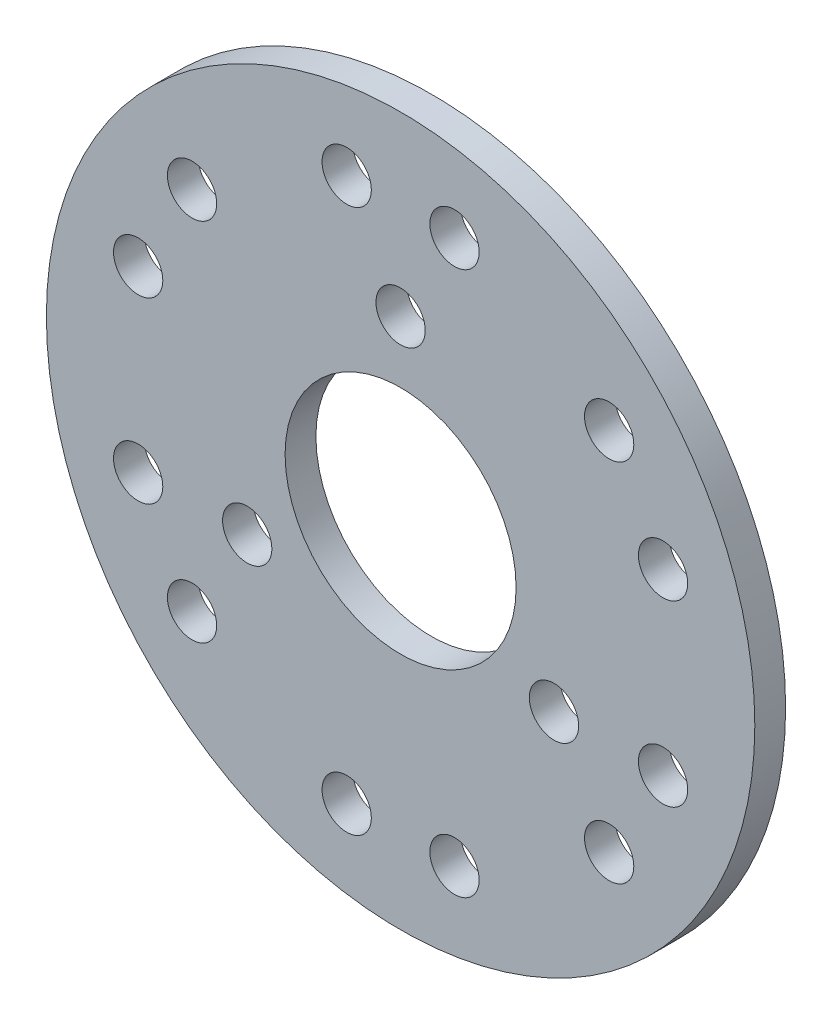
SolidWorks part; units mm, degrees
material "6061 合金"
ref_plane "正面" through (0, 0, 0) normal (0, 0, 1) x (1, 0, 0)
ref_plane "平面" through (0, 0, 0) normal (0, 1, 0) x (1, 0, 0)
ref_plane "右側面" through (0, 0, 0) normal (1, 0, 0) x (0, 0, -1)
sketch "ｽｹｯﾁ1" plane through (0, 0, 0) normal (0, 0, 1) x (1, 0, 0)
  circle A0 centre (0, 0) radius 23
  dimension "D1" = 46
extrude "ﾎﾞｽ - 押し出し1" add sketch "ｽｹｯﾁ1" along normal blind 2
sketch "ｽｹｯﾁ2" plane through (0, 0, 2) normal (0, 0, 1) x (1, 0, 0)
  line L0 (0, 0) -> (0, 23) construction
  line L1 (-3.5, 17.6564) -> (3.5, 17.6564) construction
  line L2 (0, 0) -> (19.9186, 11.5) construction
  line L3 (13.5409, 11.8593) -> (17.0409, 5.7971) construction
  line L4 (0, 0) -> (19.9186, -11.5) construction
  line L5 (17.0409, -5.7971) -> (13.5409, -11.8593) construction
  line L6 (0, 0) -> (0, -23) construction
  line L7 (3.5, -17.6564) -> (-3.5, -17.6564) construction
  line L8 (0, 0) -> (-19.9186, -11.5) construction
  line L9 (-13.5409, -11.8593) -> (-17.0409, -5.7971) construction
  line L10 (0, 0) -> (-19.9186, 11.5) construction
  line L11 (-17.0409, 5.7971) -> (-13.5409, 11.8593) construction
  circle A0 centre (0, 0) radius 23 construction
  circle A1 centre (-3.5, 17.6564) radius 1.6
  circle A2 centre (3.5, 17.6564) radius 1.6
  circle A3 centre (13.5409, 11.8593) radius 1.6
  circle A4 centre (17.0409, 5.7971) radius 1.6
  circle A5 centre (17.0409, -5.7971) radius 1.6
  circle A6 centre (13.5409, -11.8593) radius 1.6
  circle A7 centre (3.5, -17.6564) radius 1.6
  circle A8 centre (-3.5, -17.6564) radius 1.6
  circle A9 centre (-13.5409, -11.8593) radius 1.6
  circle A10 centre (-17.0409, -5.7971) radius 1.6
  circle A11 centre (-17.0409, 5.7971) radius 1.6
  circle A12 centre (-13.5409, 11.8593) radius 1.6
  circle A13 centre (0, 0) radius 7.5
  circle A14 centre (0, 11.5) radius 1.6
  circle A15 centre (-9.9593, -5.75) radius 1.6
  circle A16 centre (9.9593, -5.75) radius 1.6
  point P7 (0, 17.6564)
  point P37 (0, 0)
  dimension "D1" = 18
  dimension "D3" = 3.2
  dimension "D5" = 15
  dimension "D2" = 7
  dimension "D4" = 6
extrude "ｶｯﾄ - 押し出し1" cut sketch "ｽｹｯﾁ2" against normal through all
